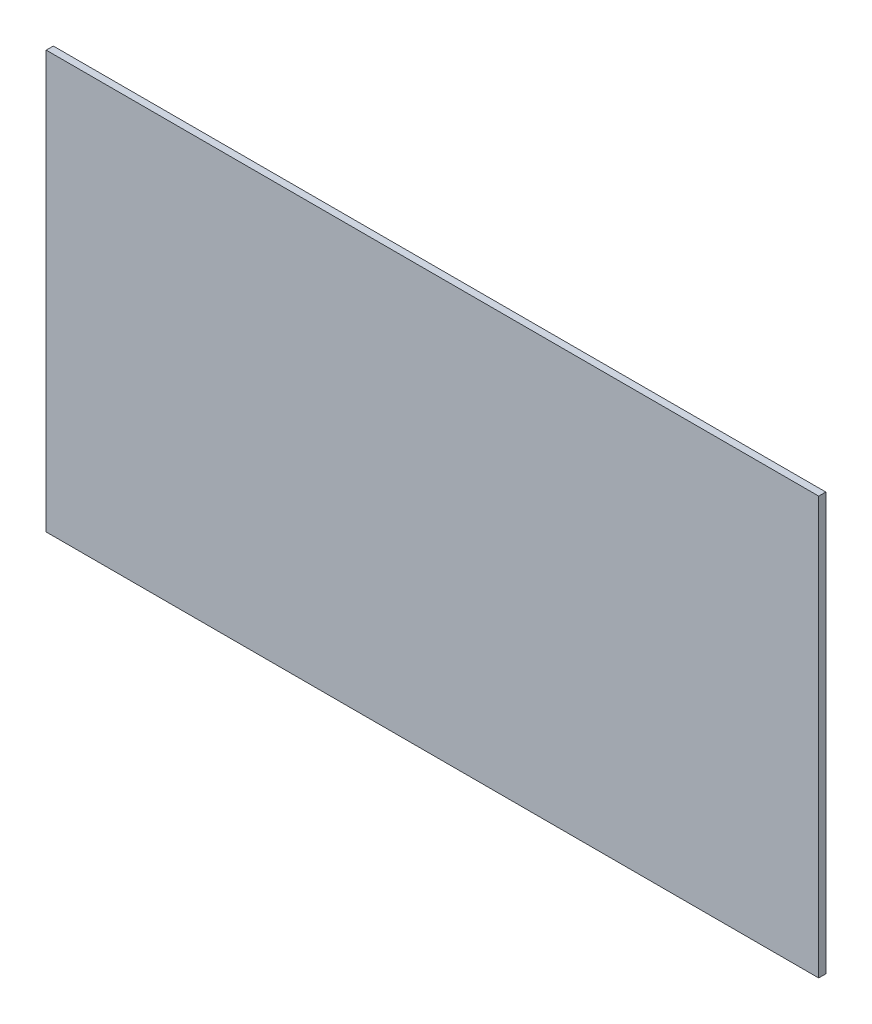
SolidWorks part; units mm, degrees
ref_plane "Ön Düzlem" through (0, 0, 0) normal (0, 0, 1) x (1, 0, 0)
ref_plane "Üst Düzlem" through (0, 0, 0) normal (0, 1, 0) x (1, 0, 0)
ref_plane "Sağ Düzlem" through (0, 0, 0) normal (1, 0, 0) x (0, 0, -1)
sketch "Sketch1" plane through (0, 0, 0) normal (0, 0, 1) x (1, 0, 0)
  line L1 (-217.5, 117.5) -> (217.5, 117.5)
  line L2 (-217.5, 117.5) -> (-217.5, -117.5)
  line L3 (-217.5, -117.5) -> (217.5, -117.5)
  line L4 (217.5, 117.5) -> (217.5, -117.5)
  line L5 (-217.5, 117.5) -> (217.5, -117.5) construction
  line L6 (-217.5, -117.5) -> (217.5, 117.5) construction
  point P0 (0, 0)
  dimension "D1" = 435
  dimension "D2" = 235
extrude "Boss-Extrude1" add sketch "Sketch1" along normal blind 4
